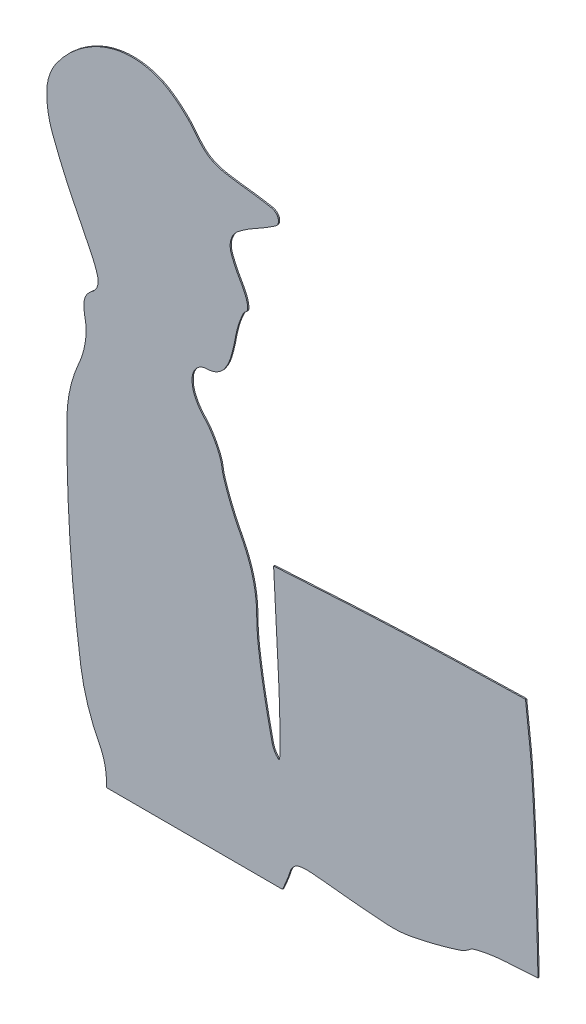
SolidWorks part; units mm, degrees
ref_plane "Front Plane" through (0, 0, 0) normal (0, 0, 1) x (1, 0, 0)
ref_plane "Top Plane" through (0, 0, 0) normal (0, 1, 0) x (1, 0, 0)
ref_plane "Right Plane" through (0, 0, 0) normal (1, 0, 0) x (0, 0, -1)
sketch "Sketch1" plane through (0, 0, 0) normal (0, 0, 1) x (1, 0, 0)
  line L8 (8159.9095, 3895.9829) -> (7421.1653, 3895.9829)
  line L9 (9214.7001, 4254.5) -> (9088.345, 4246.5253)
  line L10 (9206.6992, 4579.3689) -> (9214.7001, 4254.5)
  line L11 (9163.4249, 5219.7) -> (9181.0616, 5061.9689)
  line L12 (8909.6625, 5213.2432) -> (9163.4249, 5219.7)
  line L13 (8129.3564, 5176.3132) -> (8392.6282, 5191.5498)
  line L14 (8147.6447, 4829.7066) -> (8129.3564, 5176.3132)
  arc A84 (7587.2524, 6693.0167) -> (7669.2312, 6669.9598) centre (7551.3556, 6408.1187) cw
  arc A85 (7500.8659, 6691.5213) -> (7587.2524, 6693.0167) centre (7549.2649, 6391.5289) cw
  arc A86 (7414.1198, 6665.197) -> (7500.8659, 6691.5213) centre (7554.6334, 6358.2538) cw
  arc A87 (7331.1613, 6615.4178) -> (7414.1198, 6665.197) centre (7595.6508, 6268.6544) cw
  arc A88 (7234.099, 6512.6516) -> (7331.1613, 6615.4178) centre (7596.3784, 6267.7005) cw
  arc A89 (7198.2292, 6401.9298) -> (7234.099, 6512.6516) centre (7407.7942, 6395.2097) cw
  arc A90 (7221.5866, 6260.1456) -> (7198.2292, 6401.9298) centre (7568.2183, 6390.0654) cw
  arc A91 (7313.0512, 6050.6674) -> (7221.5866, 6260.1456) centre (9238.7137, 7016.1777) cw
  arc A92 (7313.0512, 6050.6674) -> (7384.9067, 5904.4436) centre (-1778.4534, 1492.2649) cw
  arc A93 (7384.9067, 5904.4436) -> (7407.1312, 5844.6738) centre (7074.7324, 5755.0931) cw
  arc A94 (7407.1312, 5844.6738) -> (7406.0697, 5809.4058) centre (7348.219, 5828.797) cw
  arc A95 (7406.0697, 5809.4058) -> (7385.6104, 5781.4291) centre (7351.8687, 5827.5736) cw
  arc A96 (7364.7781, 5761.1593) -> (7385.6104, 5781.4291) centre (7446.9358, 5697.5618) cw
  arc A97 (7353.3573, 5738.0738) -> (7364.7781, 5761.1593) centre (7416.2065, 5721.349) cw
  arc A98 (7350.4844, 5708.8046) -> (7353.3573, 5738.0738) centre (7441.3331, 5714.6628) cw
  arc A99 (7355.7138, 5669.0817) -> (7350.4844, 5708.8046) centre (7651.3203, 5728.2031) cw
  arc A100 (7355.7138, 5669.0817) -> (7359.5786, 5629.3709) centre (7160.4998, 5630.039) cw
  arc A101 (7359.5786, 5629.3709) -> (7356.1181, 5585.5978) centre (7068.6427, 5630.3478) cw
  arc A102 (7356.1181, 5585.5978) -> (7345.6205, 5539.7491) centre (7026.9524, 5636.8379) cw
  arc A103 (7345.6205, 5539.7491) -> (7328.4315, 5493.82) centre (6969.3511, 5654.3872) cw
  arc A104 (7280.7323, 5273.9712) -> (7328.4315, 5493.82) centre (7828.4345, 5270.2385) cw
  arc A105 (7293.3567, 4849.0368) -> (7280.7323, 5273.9712) centre (13103.2555, 5234.2989) cw
  arc A106 (7338.0949, 4424.0105) -> (7293.3567, 4849.0368) centre (12810.0795, 5214.8581) cw
  arc A107 (7415.3424, 4183.1831) -> (7338.0949, 4424.0105) centre (8091.6637, 4532.9216) cw
  arc A108 (7415.3424, 4183.1831) -> (7430.9135, 4145.2165) centre (7208.0765, 4076.0017) cw
  arc A109 (7430.9135, 4145.2165) -> (7440.2746, 4103.7376) centre (7174.2556, 4065.497) cw
  arc A110 (7440.2746, 4103.7376) -> (7443.133, 4060.2222) centre (7160.3542, 4063.4988) cw
  arc A111 (7443.133, 4060.2222) -> (7439.3471, 4016.195) centre (7145.0809, 4063.6756) cw
  arc A112 (7421.1653, 3895.9829) -> (7439.3471, 4016.195) centre (13524.3085, 3034.3769) cw
  arc A113 (8159.9095, 3895.9829) -> (8153.5208, 3936.7724) centre (8542.0522, 3976.7318) cw
  arc A114 (8153.5208, 3936.7724) -> (8151.5328, 3977.7264) centre (8531.4828, 3975.6451) cw
  arc A115 (8151.5328, 3977.7264) -> (8153.723, 4013.3099) centre (8470.0087, 3975.9824) cw
  arc A116 (8153.723, 4013.3099) -> (8160.6746, 4035.6829) centre (8217.3807, 4005.7971) cw
  arc A117 (8170.0441, 4054.8374) -> (8160.6746, 4035.6829) centre (7847.3143, 4200.833) cw
  arc A118 (8180.3702, 4078.7176) -> (8170.0441, 4054.8374) centre (7460.2781, 4375.9196) cw
  arc A119 (8190.0287, 4103.2702) -> (8180.3702, 4078.7176) centre (7447.5821, 4381.1584) cw
  arc A120 (8197.3672, 4124.5857) -> (8190.0287, 4103.2702) centre (7792.74, 4251.9707) cw
  arc A121 (8197.3672, 4124.5857) -> (8212.9227, 4149.5388) centre (8253.5135, 4106.9097) cw
  arc A122 (8212.9227, 4149.5388) -> (8237.6323, 4161.7465) centre (8244.8683, 4115.989) cw
  arc A123 (8237.6323, 4161.7465) -> (8282.6969, 4163.4772) centre (8267.4356, 3973.2847) cw
  arc A124 (8282.6969, 4163.4772) -> (8383.3713, 4154.0003) centre (7989.3859, 508.1117) cw
  arc A125 (8453.4683, 4146.8809) -> (8383.3713, 4154.0003) centre (8972.1898, 9602.857) cw
  arc A126 (8522.7429, 4140.7617) -> (8453.4683, 4146.8809) centre (8945.8534, 9325.8822) cw
  arc A127 (8582.7243, 4136.2556) -> (8522.7429, 4140.7617) centre (8902.7989, 8798.2968) cw
  arc A128 (8617.8001, 4134.8709) -> (8582.7243, 4136.2556) centre (8624.0559, 4738.2784) cw
  arc A129 (8689.6476, 4141.1442) -> (8617.8001, 4134.8709) centre (8621.6422, 4505.4368) cw
  arc A130 (8792.163, 4163.8161) -> (8689.6476, 4141.1442) centre (8398.5446, 5700.5332) cw
  arc A131 (8890.9451, 4192.0847) -> (8792.163, 4163.8161) centre (8336.3503, 5943.3372) cw
  arc A132 (8934.945, 4216.1053) -> (8890.9451, 4192.0847) centre (8851.4955, 4316.6557) cw
  arc A133 (8934.945, 4216.1053) -> (8952.6858, 4225.3013) centre (8964.9213, 4179.986) cw
  arc A134 (8952.6858, 4225.3013) -> (8991.1623, 4234.2999) centre (9104.2955, 3663.8) cw
  arc A135 (8991.1623, 4234.2999) -> (9037.9851, 4241.827) centre (9118.0021, 3594.6818) cw
  arc A136 (9037.9851, 4241.827) -> (9088.345, 4246.5253) centre (9141.4583, 3404.977) cw
  arc A137 (9202.3418, 4715.3151) -> (9206.6992, 4579.3689) centre (41.3843, 4353.6384) cw
  arc A138 (9195.8678, 4855.1411) -> (9202.3418, 4715.3151) centre (-1073.0386, 4309.6255) cw
  arc A139 (9188.3938, 4979.817) -> (9195.8678, 4855.1411) centre (27.5885, 4368.0862) cw
  arc A140 (9181.0616, 5061.9689) -> (9188.3938, 4979.817) centre (7346.119, 4856.7947) cw
  arc A141 (8793.4904, 5209.6764) -> (8909.6625, 5213.2432) centre (9191.003, -5844.0459) cw
  arc A142 (8653.1067, 5204.2073) -> (8793.4904, 5209.6764) centre (9636.653, -18237.1844) cw
  arc A172 (8511.8218, 5197.8562) -> (8653.1067, 5204.2073) centre (9644.5089, -18425.1544) cw
  arc A173 (8392.6282, 5191.5498) -> (8511.8218, 5197.8562) centre (9089.2377, -6844.9772) cw
  arc A174 (8147.6447, 4829.7066) -> (8153.3609, 4697.9877) centre (1103.8499, 4458.0428) cw
  arc A175 (8153.3609, 4697.9877) -> (8155.2061, 4590.1089) centre (4966.9821, 4589.532) cw
  arc A176 (8155.2061, 4590.1089) -> (8154.4911, 4503.5849) centre (3031.5352, 4589.183) cw
  arc A177 (8154.4911, 4503.5849) -> (8147.7041, 4500.7791) centre (8150.4901, 4503.6517) cw
  arc A178 (8147.7041, 4500.7791) -> (8123.5691, 4543.9065) centre (8207.7637, 4562.7067) cw
  arc A179 (8123.5691, 4543.9065) -> (8092.7445, 4693.8243) centre (12541.1818, 5530.34) cw
  arc A180 (8092.7445, 4693.8243) -> (8068.0762, 4848.5941) centre (10861.4995, 5214.4794) cw
  arc A181 (8068.0762, 4848.5941) -> (8059.8924, 4967.7453) centre (9028.916, 4974.4452) cw
  arc A182 (8055.4845, 5032.8568) -> (8059.8924, 4967.7453) centre (7521.826, 4964.0247) cw
  arc A183 (8043.2341, 5095.7946) -> (8055.4845, 5032.8568) centre (7558.069, 4968.6991) cw
  arc A184 (8022.6625, 5158.2039) -> (8043.2341, 5095.7946) centre (7531.9447, 4961.8564) cw
  arc A185 (7993.354, 5221.7453) -> (8022.6625, 5158.2039) centre (7392.3486, 4906.0012) cw
  arc A186 (7993.354, 5221.7453) -> (7967.4417, 5275.0801) centre (8827.4722, 5659.9563) cw
  arc A187 (7967.4417, 5275.0801) -> (7943.8639, 5331.9985) centre (8969.4621, 5723.4982) cw
  arc A188 (7943.8639, 5331.9985) -> (7925.5647, 5384.362) centre (8854.5417, 5679.6284) cw
  arc A189 (7925.5647, 5384.362) -> (7917.0612, 5421.6069) centre (8144.4146, 5453.9211) cw
  arc A190 (7908.4889, 5455.0189) -> (7917.0612, 5421.6069) centre (7761.4615, 5399.4914) cw
  arc A191 (7891.1656, 5493.6909) -> (7908.4889, 5455.0189) centre (7578.1839, 5330.2731) cw
  arc A192 (7868.5908, 5531.3279) -> (7891.1656, 5493.6909) centre (7561.7164, 5321.675) cw
  arc A193 (7843.8564, 5561.8106) -> (7868.5908, 5531.3279) centre (7671.4845, 5396.6676) cw
  arc A194 (7843.8564, 5561.8106) -> (7805.5567, 5618.8129) centre (7988.4165, 5700.3081) cw
  arc A195 (7805.5567, 5618.8129) -> (7794.8476, 5678.8056) centre (7921.4116, 5670.446) cw
  arc A196 (7794.8476, 5678.8056) -> (7814.1113, 5722.6293) centre (7864.8457, 5674.1821) cw
  arc A197 (7814.1113, 5722.6293) -> (7855.6525, 5740.4) centre (7855.6525, 5682.9608) cw
  arc A198 (7896.7366, 5750.43) -> (7855.6525, 5740.4) centre (7855.6525, 5829.558) cw
  arc A199 (7928.5329, 5778.2579) -> (7896.7366, 5750.43) centre (7855.7875, 5829.298) cw
  arc A200 (7952.7428, 5828.0375) -> (7928.5329, 5778.2579) centre (7785.5736, 5878.562) cw
  arc A201 (7971.4909, 5905.5) -> (7952.7428, 5828.0375) centre (7271.7702, 6033.8517) cw
  arc A202 (7971.4909, 5905.5) -> (7980.4886, 5945.6062) centre (8486.2842, 5811.0707) cw
  arc A203 (7980.4886, 5945.6062) -> (7992.1157, 5982.092) centre (8361.8814, 5844.1607) cw
  arc A204 (7992.1157, 5982.092) -> (8004.5573, 6011.1505) centre (8303.9535, 5865.7695) cw
  arc A205 (8004.5573, 6011.1505) -> (8015.5323, 6023.5663) centre (8032.3164, 5997.6713) cw
  arc A206 (8022.7395, 6036.047) -> (8015.5323, 6023.5663) centre (8006.9124, 6036.8653) cw
  arc A207 (8020.6239, 6058.4707) -> (8022.7395, 6036.047) centre (7945.287, 6040.0513) cw
  arc A208 (8009.9696, 6088.6654) -> (8020.6239, 6058.4707) centre (7863.9553, 6020.1666) cw
  arc A209 (7990.6919, 6125.1663) -> (8009.9696, 6088.6654) centre (7614.5068, 5903.1448) cw
  arc A210 (7990.6919, 6125.1663) -> (7956.0496, 6198.0891) centre (8378.8354, 6354.2453) cw
  arc A211 (7956.0496, 6198.0891) -> (7954.1513, 6249.1069) centre (8032.9567, 6226.4949) cw
  arc A212 (7954.1513, 6249.1069) -> (7982.8462, 6291.9528) centre (8035.2189, 6225.8458) cw
  arc A213 (7982.8462, 6291.9528) -> (8051.6056, 6337.4574) centre (8283.0919, 5912.9704) cw
  arc A214 (8137.129, 6389.3586) -> (8051.6056, 6337.4574) centre (7533.0628, 7288.3323) cw
  arc A215 (8148.3282, 6420.9851) -> (8137.129, 6389.3586) centre (8121.4371, 6412.7114) cw
  arc A216 (8121.0412, 6445.4046) -> (8148.3282, 6420.9851) centre (8114.4225, 6410.5532) cw
  arc A217 (8013.3811, 6461.6943) -> (8121.0412, 6445.4046) centre (7850.1722, 5019.1215) cw
  arc A218 (8013.3811, 6461.6943) -> (7930.6413, 6473.8521) centre (8154.8395, 7712.0111) cw
  arc A219 (7930.6413, 6473.8521) -> (7880.721, 6489.5205) centre (7968.0296, 6680.3311) cw
  arc A220 (7880.721, 6489.5205) -> (7843.6261, 6514.5743) centre (7937.4535, 6613.5077) cw
  arc A221 (7843.6261, 6514.5743) -> (7806.7763, 6556.2299) centre (8062.2987, 6745.1458) cw
  arc A222 (7778.9569, 6588.6033) -> (7806.7763, 6556.2299) centre (7572.2746, 6382.8555) cw
  arc A223 (7742.6892, 6621.6714) -> (7778.9569, 6588.6033) centre (7419.34, 6230.6128) cw
  arc A224 (7704.0838, 6650.5457) -> (7742.6892, 6621.6714) centre (7427.3186, 6240.2616) cw
  arc A225 (7669.2312, 6669.9598) -> (7704.0838, 6650.5457) centre (7573.036, 6456.2772) cw
extrude "Boss-Extrude1" add sketch "Sketch1" along normal blind 5
scale "Scale1" scale about centroid uniform scaling yes scale factor 0.25
sketch "Sketch2" plane through (0, 0, 3.125) normal (0, 0, 1) x (1, 0, 0)
  line L0 (7883.5579, 4786.5623) -> (8064.2802, 4786.4187)
  line L1 (8064.2802, 4786.4187) -> (8074.9285, 4737.6021)
  line L2 (8074.9285, 4737.6021) -> (7845.0163, 4737.6021)
  line L3 (7845.0163, 4737.6021) -> (7883.5579, 4786.5623)
  arc A0 (7882.7411, 4779.17) -> (7883.6875, 4790.1768) centre (7809.1745, 4791.0402) ccw construction
  arc A1 (8063.0729, 4784.042) -> (8065.4153, 4788.8306) centre (7984.7329, 4825.3295) ccw construction
extrude "Cut-Extrude1" cut sketch "Sketch2" against normal through all
